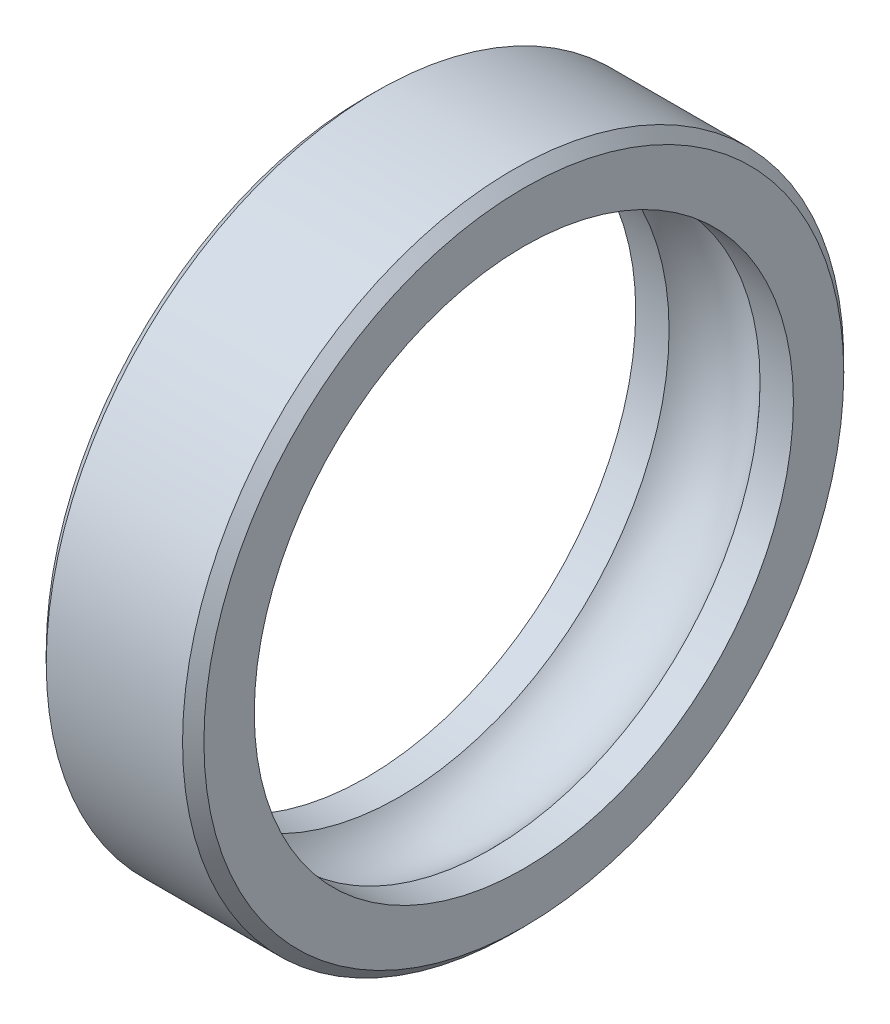
SolidWorks part; units mm, degrees
ref_plane "Front Plane" through (0, 0, 0) normal (0, 0, 1) x (1, 0, 0)
ref_plane "Top Plane" through (0, 0, 0) normal (0, 1, 0) x (1, 0, 0)
ref_plane "Right Plane" through (0, 0, 0) normal (1, 0, 0) x (0, 0, -1)
sketch "Sketch1" plane through (0, 0, 0) normal (0, 0, 1) x (1, 0, 0)
  line L0 (-15.9982, 0) -> (19.0982, 0) construction
  line L1 (0, 53) -> (0, 0) construction
  line L2 (15.5, 53) -> (8.9443, 53)
  line L3 (15.5, 53) -> (15.5, 65)
  line L4 (15.5, 65) -> (-15.5, 65)
  line L5 (-15.5, 53) -> (-15.5, 65)
  line L6 (15.5, 53) -> (-15.5, 65) construction
  line L7 (15.5, 65) -> (-15.5, 53) construction
  line L8 (-8.9443, 53) -> (-15.5, 53)
  arc A0 (-8.9443, 53) -> (8.9443, 53) centre (0, 45) cw
  point P3 (0, 59)
  point P13 (0, 0)
  point P14 (0, 0)
  dimension "D1" = 31
  dimension "D2" = 53
  dimension "D3" = 65
  dimension "D4" = 8
  dimension "D5" = 12
  dimension "D6" = 6.5557
revolve "Revolve1" add sketch "Sketch1" angle 360 about L0
chamfer "Chamfer1" distance 2.1 angle 45 2 edges at (15.5, 0, 65) (-15.5, 0, 65)
